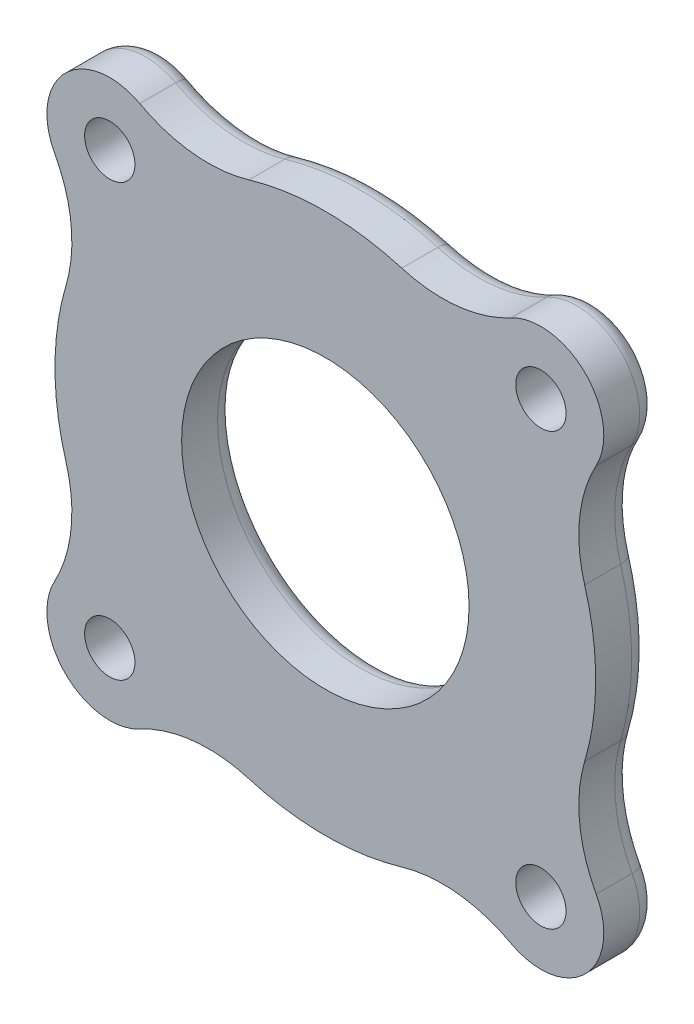
SolidWorks part; units mm, degrees
ref_plane "Front Plane" through (0, 0, 0) normal (0, 0, 1) x (1, 0, 0)
ref_plane "Top Plane" through (0, 0, 0) normal (0, 1, 0) x (1, 0, 0)
ref_plane "Right Plane" through (0, 0, 0) normal (1, 0, 0) x (0, 0, -1)
sketch "Sketch2" plane through (0, 0, 0) normal (0, 0, 1) x (1, 0, 0)
  circle A0 centre (16.8042, -30.0086) radius 8
  arc A2 (2.3685, -25.7528) -> (2.3685, -34.2643) centre (16.8042, -30.0086) ccw
  arc A3 (2.2395, -26.2176) -> (2.2395, -33.7996) centre (16.8042, -30.0086) ccw construction
  circle A4 centre (4.8042, -18.0086) radius 1.4
  circle A5 centre (28.8042, -18.0086) radius 1.4
  circle A6 centre (28.8042, -42.0086) radius 1.4
  circle A7 centre (4.8042, -42.0086) radius 1.4
  arc A8 (6.4727, -14.9318) -> (1.7275, -19.677) centre (4.8042, -18.0086) ccw
  arc A9 (31.8809, -19.677) -> (27.1358, -14.9318) centre (28.8042, -18.0086) ccw
  arc A10 (27.1358, -45.0853) -> (31.8809, -40.3401) centre (28.8042, -42.0086) ccw
  arc A11 (1.7275, -40.3401) -> (6.4727, -45.0853) centre (4.8042, -42.0086) ccw
  arc A12 (21.06, -15.5728) -> (12.5485, -15.5728) centre (16.8042, -30.0086) ccw
  arc A13 (31.24, -34.2643) -> (31.24, -25.7528) centre (16.8042, -30.0086) ccw
  arc A14 (12.5485, -44.4443) -> (21.06, -44.4443) centre (16.8042, -30.0086) ccw
  arc A15 (1.7275, -19.677) -> (2.3685, -25.7528) centre (-5.305, -23.4906) cw
  arc A16 (2.3685, -34.2643) -> (1.7275, -40.3401) centre (-5.305, -36.5265) cw
  arc A17 (6.4727, -45.0853) -> (12.5485, -44.4443) centre (10.2863, -52.1178) cw
  arc A18 (21.06, -44.4443) -> (27.1358, -45.0853) centre (23.3221, -52.1178) cw
  arc A19 (31.24, -34.2643) -> (31.8809, -40.3401) centre (38.9135, -36.5265) ccw
  arc A20 (31.8809, -19.677) -> (31.24, -25.7528) centre (38.9135, -23.4906) ccw
  arc A21 (27.1358, -14.9318) -> (21.06, -15.5728) centre (23.3221, -7.8993) cw
  arc A22 (6.4727, -14.9318) -> (12.5485, -15.5728) centre (10.2863, -7.8993) ccw
  dimension "D1" = 8
  dimension "D2" = 16
extrude "Boss-Extrude1" add sketch "Sketch2" along normal blind 3
fillet "Fillet1" radius 1 17 edges at (30.9576, -37.3658, 0) (31.2791, -44.4834, 0) (24.1615, -44.162, 0) (16.8042, -45.0586, 0) (9.447, -44.162, 0) (2.3293, -44.4834, 0) (2.6508, -37.3658, 0) (1.7542, -30.0086, 0) (2.6508, -22.6513, 0) (2.3293, -15.5337, 0) (9.447, -15.8552, 0) (16.8042, -14.9586, 0) (24.1615, -15.8552, 0) (31.2791, -15.5337, 0) (30.9576, -22.6513, 0) (31.8542, -30.0086, 0) (24.8042, -30.0086, 0)
